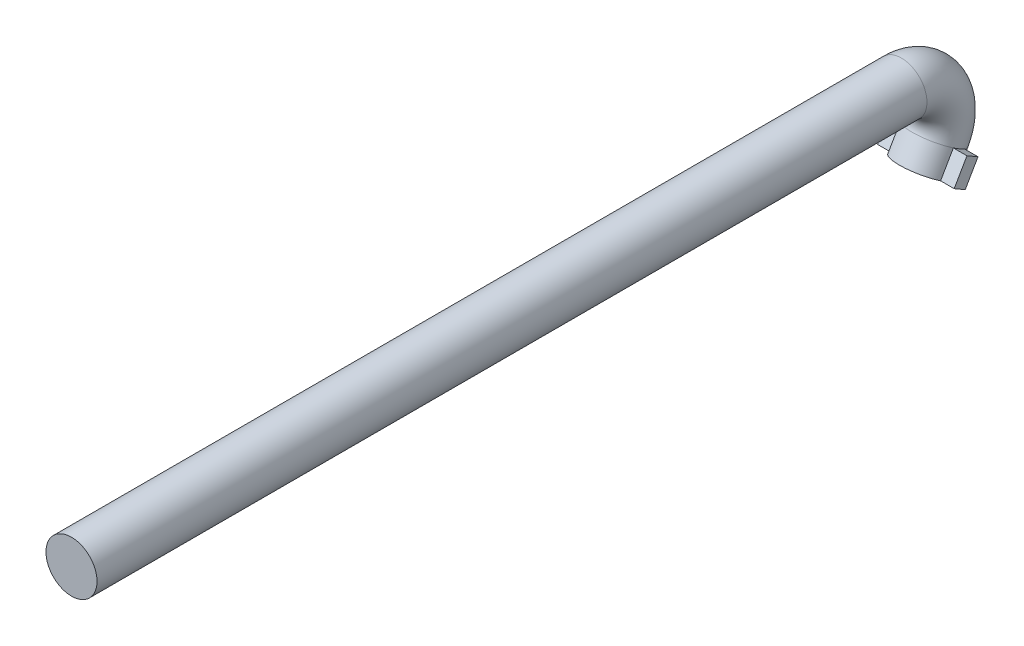
SolidWorks part; units mm, degrees
ref_plane "Front" through (0, 0, 0) normal (0, 0, 1) x (1, 0, 0)
ref_plane "Top" through (0, 0, 0) normal (0, 1, 0) x (1, 0, 0)
ref_plane "Right" through (0, 0, 0) normal (1, 0, 0) x (0, 0, -1)
sketch "Sketch1" plane through (0, 0, 0) normal (0, 0, 1) x (1, 0, 0)
  circle A0 centre (0, 0) radius 2
  dimension "D1" = 4
extrude "Boss-Extrude1" add sketch "Sketch1" along normal blind 65
sketch "Sketch4" plane through (0, 0, 0) normal (0, 0, -1) x (-1, 0, 0)
  line L0 (0, -2) -> (1.8096, -2)
  circle A0 centre (0, 0) radius 2 construction
ref_plane "Plane2" through (0, -0.5, 0.866) normal (0, 0.5, -0.866) x (-1, 0, 0)
sketch "Sketch8" plane through (0, 0, 0) normal (0, 0, -1) x (-1, 0, 0)
  circle A1 centre (0, 0) radius 2
  circle A2 centre (0, 0) radius 2
  dimension "D1" = 0
sketch "Sketch11" plane through (0, 0, 0) normal (0, 0, -1) x (-1, 0, 0)
  line L1 (0, -2.964) -> (1.1897, -2.964)
revolve "Revolve4" add sketch "Sketch8" angle 120 about L1
sketch "Sketch12" plane through (0, -2.223, 1.2835) normal (0, -0.866, 0.5) x (1, 0, 0)
  line L1 (2, -4.946) -> (1.9365, -4.946)
  line L4 (-2, -4.946) -> (-3, -4.946)
  line L5 (-2, -3.946) -> (-3, -3.946)
  line L6 (-3, -4.946) -> (-3, -3.946)
  line L7 (-2, -4.946) -> (-1.9365, -4.946)
  line L8 (-2, -3.946) -> (-1.9365, -3.946)
  line L9 (2, -3.946) -> (1.9365, -3.946)
  line L10 (2, -3.946) -> (3, -3.946)
  line L11 (3, -4.946) -> (3, -3.946)
  line L12 (2, -4.946) -> (3, -4.946)
  arc A0 (1.9365, -3.946) -> (-1.9365, -3.946) centre (0, -4.446) ccw
  circle A1 centre (0, -4.446) radius 2
  arc A2 (-1.9365, -4.946) -> (1.9365, -4.946) centre (0, -4.446) ccw
  dimension "D3" = 1
  dimension "D1" = 0
extrude "Boss-Extrude3" add sketch "Sketch12" along normal blind 2
